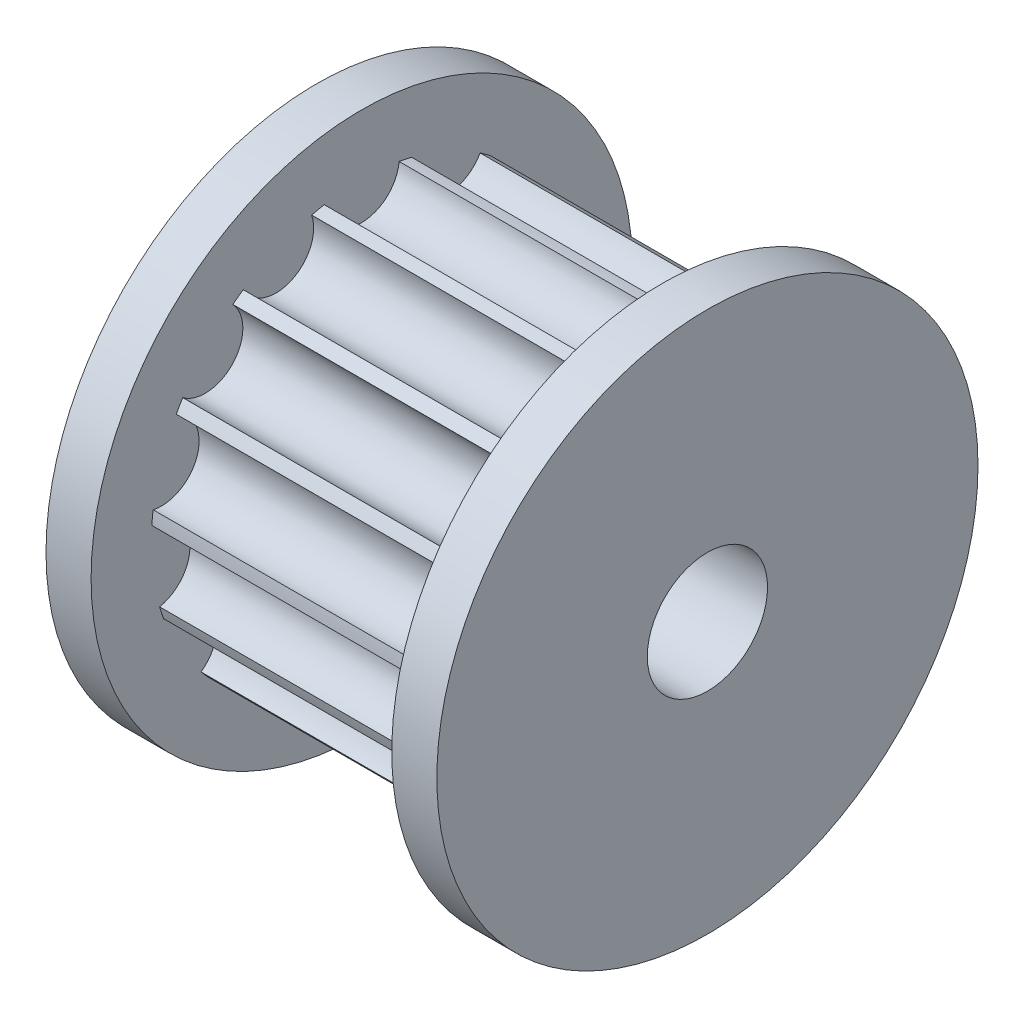
SolidWorks part; units mm, degrees
ref_plane "前视基准面" through (0, 0, 0) normal (0, 0, 1) x (1, 0, 0)
ref_plane "上视基准面" through (0, 0, 0) normal (0, 1, 0) x (1, 0, 0)
ref_plane "右视基准面" through (0, 0, 0) normal (1, 0, 0) x (0, 0, -1)
sketch "草图1" plane through (0, 0, 0) normal (0, 0, 1) x (1, 0, 0)
  line L0 (-27.3637, 8.8472) -> (-27.3637, 3.8472)
  line L1 (-27.3637, 3.8472) -> (-28.6137, 3.8472)
  line L2 (-28.6137, 3.8472) -> (-28.6137, 1.8472)
  line L3 (-17.3637, 8.8472) -> (-27.3637, 8.8472)
  line L4 (-48.9645, 1.8472) -> (-7.7326, 1.8472) construction
  line L6 (-28.6137, 1.8472) -> (-16.1137, 1.8472)
  line L8 (-17.3637, 8.8472) -> (-17.3637, 3.8472)
  line L9 (-16.1137, 3.8472) -> (-16.1137, 1.8472)
  line L10 (-17.3637, 3.8472) -> (-16.1137, 3.8472)
  dimension "D1" = 10
  dimension "D2" = 7
  dimension "D3" = 2
  dimension "D4" = 1.25
revolve "旋转2" add sketch "草图1" angle 360 about L4
sketch "草图3" plane through (-28.6137, 0, 0) normal (-1, 0, 0) x (0, 0, 1)
  circle A0 centre (0, 1.8472) radius 2
  dimension "D1" = 4
extrude "切除-拉伸2" cut sketch "草图3" against normal blind 17
sketch "草图4" plane through (-27.3637, 0, 0) normal (-1, 0, 0) x (0, 0, 1)
  line L1 (-1.25, 8.8472) -> (1.25, 8.8472)
  line L2 (-1.25, 8.8472) -> (-1.25, 11.5305)
  line L3 (-1.25, 11.5305) -> (1.25, 11.5305)
  line L4 (1.25, 8.8472) -> (1.25, 11.5305)
  arc A0 (-1.25, 8.8472) -> (1.25, 8.8472) centre (0, 8.8472) ccw
  circle A1 centre (0, 1.8472) radius 7 construction
  circle M7 centre (0, 1.8472) radius 7
  dimension "D1" = 2.5
extrude "切除-拉伸3" cut sketch "草图4" against normal blind 17 contours A0 M7
pattern_circular "阵列(圆周)1" count 15 over 360 about axis through (0, 1.8472, 0) along (1, 0, 0) of "切除-拉伸3"
sketch "草图5" plane through (-27.3637, 0, 0) normal (-1, 0, 0) x (0, 0, 1)
  circle A0 centre (0, 1.8472) radius 9
  circle A1 centre (0, 1.8472) radius 2 construction
  circle A2 centre (0, 1.8472) radius 2
  dimension "D1" = 18
extrude "凸台-拉伸1" add sketch "草图5" along normal blind 1.5
sketch "草图6" plane through (-17.3637, 0, 0) normal (1, 0, 0) x (0, 0, -1)
  circle A0 centre (0, 1.8472) radius 2 construction
  circle A1 centre (0, 1.8472) radius 9
  circle A2 centre (0, 1.8472) radius 9
  circle A3 centre (0, 1.8472) radius 2
  dimension "D1" = 0
extrude "凸台-拉伸2" add sketch "草图6" along normal blind 1.5
